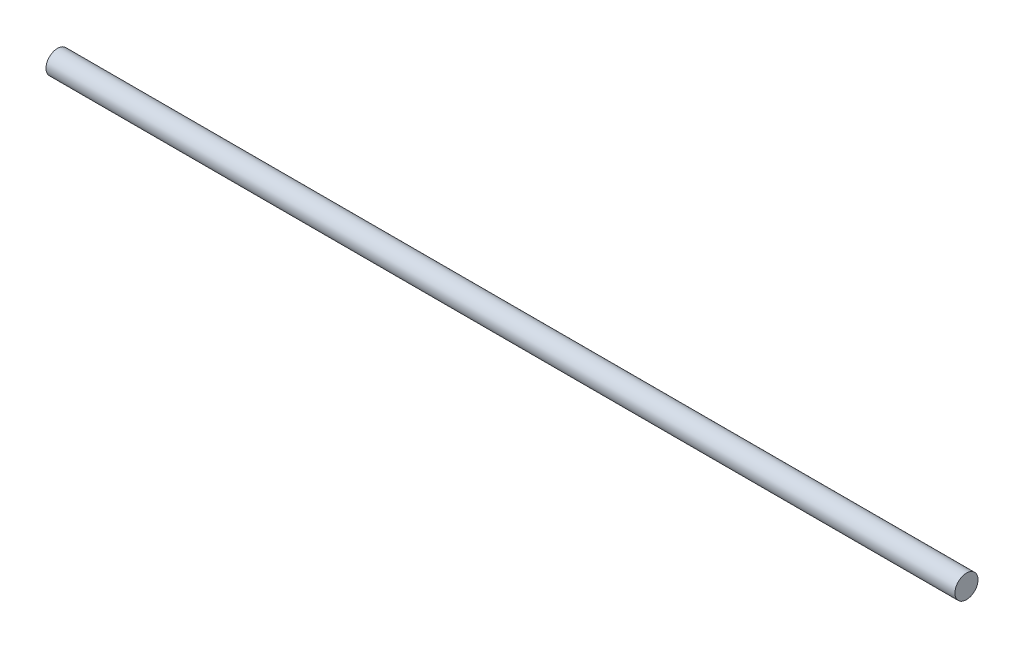
SolidWorks part; units mm, degrees
ref_plane "Front Plane" through (0, 0, 0) normal (0, 0, 1) x (1, 0, 0)
ref_plane "Top Plane" through (0, 0, 0) normal (0, 1, 0) x (1, 0, 0)
ref_plane "Right Plane" through (0, 0, 0) normal (1, 0, 0) x (0, 0, -1)
sketch "Sketch1" plane through (0, 0, 0) normal (1, 0, 0) x (0, 0, -1)
  circle A0 centre (0, 0) radius 12.7
  dimension "D1" = 25.4
extrude "Boss-Extrude1" add sketch "Sketch1" along normal blind 1000
